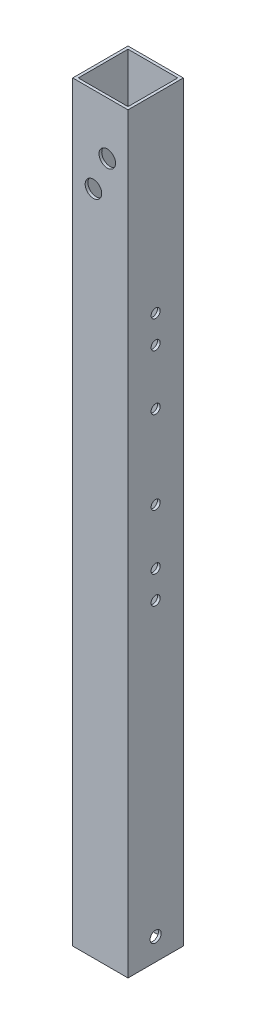
SolidWorks part; units mm, degrees
ref_plane "前视基准面" through (0, 0, 0) normal (0, 0, 1) x (1, 0, 0)
ref_plane "上视基准面" through (0, 0, 0) normal (0, 1, 0) x (1, 0, 0)
ref_plane "右视基准面" through (0, 0, 0) normal (1, 0, 0) x (0, 0, -1)
other "Configuration Table"
sketch "草图1" plane through (0, 0, 0) normal (0, 1, 0) x (1, 0, 0)
  line L1 (-9, 9) -> (9, 9)
  line L2 (-9, 9) -> (-9, -9)
  line L3 (-9, -9) -> (9, -9)
  line L4 (9, 9) -> (9, -9)
  line L5 (-9, 9) -> (9, -9) construction
  line L6 (-9, -9) -> (9, 9) construction
  line L7 (-10, 10) -> (10, 10)
  line L8 (-10, 10) -> (-10, -10)
  line L9 (-10, -10) -> (10, -10)
  line L10 (10, 10) -> (10, -10)
  line L11 (-10, 10) -> (10, -10) construction
  line L12 (-10, -10) -> (10, 10) construction
  point P0 (0, 0)
  point P6 (0, 0)
  dimension "D1" = 20
  dimension "D2" = 20
  dimension "D3" = 18
  dimension "D4" = 18
extrude "凸台-拉伸1" add sketch "草图1" along normal mid plane 272
sketch "草图2" plane through (0, 0, 10) normal (0, 0, 1) x (1, 0, 0)
  line L0 (0, 0) -> (0, 20) construction
  line L2 (-10, 136) -> (10, 136) construction
  circle A0 centre (-2.5, 105) radius 3
  circle A1 centre (2.5, 117) radius 3
  dimension "D5" = 6
  dimension "D6" = 6
  dimension "D1" = 19
  dimension "D2" = 12
  dimension "D3" = 2.5
  dimension "D4" = 5
extrude "切除-拉伸1" cut sketch "草图2" against normal blind 200
sketch "草图3" plane through (-10, 0, 0) normal (-1, 0, 0) x (0, 0, 1)
  line L0 (-10, 136) -> (10, 136) construction
  line L1 (0, 57.2863) -> (0, -12.7137) construction
  line L2 (0, 22.2863) -> (15.2904, 22.2863) construction
  circle A1 centre (0, -128) radius 2
  circle A8 centre (0, 57.2863) radius 1.65
  circle A9 centre (0, 67.2863) radius 1.65
  circle A10 centre (0, -12.7137) radius 1.65
  circle A11 centre (0, -22.7137) radius 1.65
  circle A12 centre (0, 37.2863) radius 1.65
  circle A13 centre (0, 7.2863) radius 1.65
  point P18 (0, 22.2863)
  dimension "D1" = 4
  dimension "D6" = 3.3
  dimension "D7" = 3.3
  dimension "D8" = 10
  dimension "D9" = 10
  dimension "D10" = 3.3
  dimension "D4" = 3.3
  dimension "D3" = 3.3
  dimension "D5" = 3.3
  dimension "D2" = 264
  dimension "D11" = 15
  dimension "D12" = 15
  dimension "D13" = 70
extrude "切除-拉伸2" cut sketch "草图3" against normal through all
